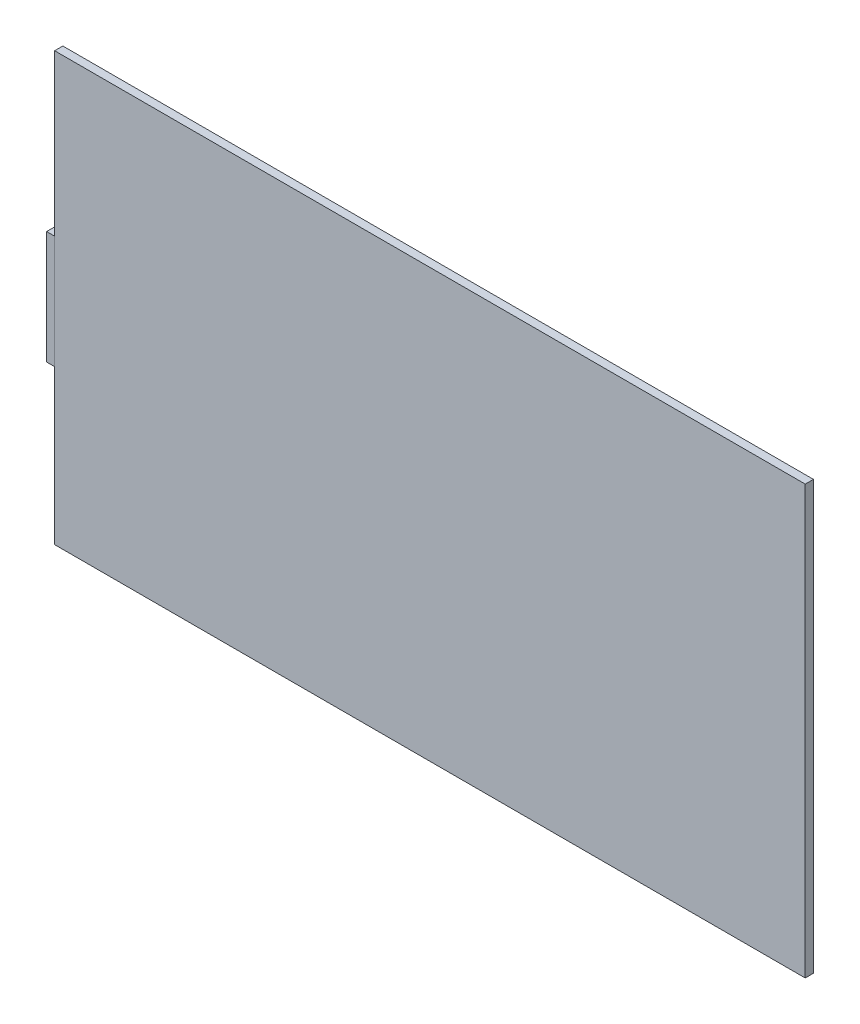
SolidWorks part; units mm, degrees
ref_plane "Front Plane" through (0, 0, 0) normal (0, 0, 1) x (1, 0, 0)
ref_plane "Top Plane" through (0, 0, 0) normal (0, 1, 0) x (1, 0, 0)
ref_plane "Right Plane" through (0, 0, 0) normal (1, 0, 0) x (0, 0, -1)
sketch "Sketch1" plane through (0, 0, 0) normal (0, 0, 1) x (1, 0, 0)
  line L1 (0, 0) -> (93, 0)
  line L2 (0, 0) -> (0, 53)
  line L3 (0, 53) -> (93, 53)
  line L4 (93, 0) -> (93, 53)
  dimension "D1" = 93
  dimension "D2" = 53
extrude "Boss-Extrude1" add sketch "Sketch1" along normal blind 1.016
sketch "Sketch2" plane through (0, 0, 1.016) normal (0, 0, 1) x (1, 0, 0)
  line L0 (0, 53) -> (0, 0) construction
  line L1 (0, 33.1) -> (-1, 33.1)
  line L2 (0, 33.1) -> (0, 19.1)
  line L3 (0, 19.1) -> (-1, 19.1)
  line L4 (-1, 33.1) -> (-1, 19.1)
  line L6 (0, 0) -> (93, 0) construction
  dimension "D1" = 14
  dimension "D2" = 1
  dimension "D3" = 19.1
extrude "Boss-Extrude2" add sketch "Sketch2" against normal up to surface (1.016 mm away) separate body contours L2 L1 L4 L3 up to face at (46.5, 26.5, 0)
